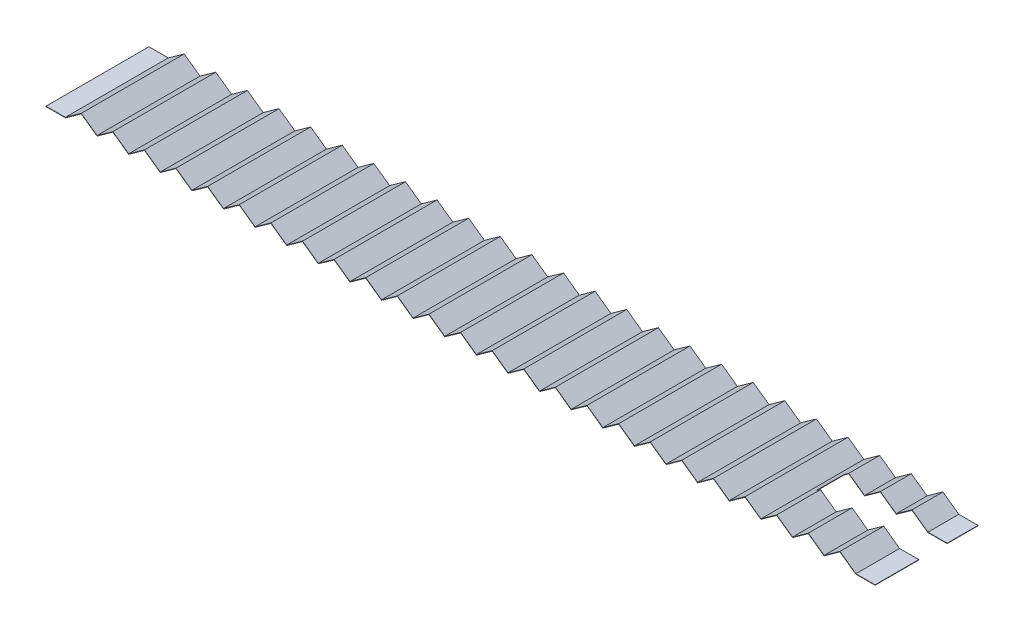
SolidWorks part; units mm, degrees
ref_plane "Front Plane" through (0, 0, 0) normal (0, 0, 1) x (1, 0, 0)
ref_plane "Top Plane" through (0, 0, 0) normal (0, 1, 0) x (1, 0, 0)
ref_plane "Right Plane" through (0, 0, 0) normal (1, 0, 0) x (0, 0, -1)
sketch "Sketch1" plane through (0, 0, 0) normal (0, 0, 1) x (1, 0, 0)
  line L0 (0, 0) -> (12.283, 8.7828)
  line L1 (12.283, 8.7828) -> (24.566, 0)
  line L2 (0, 0) -> (511, 0) construction
  line L3 (24.566, 0) -> (36.849, 8.7828)
  line L4 (36.849, 8.7828) -> (49.132, 0)
  line L5 (49.132, 0) -> (61.415, 8.7828)
  line L6 (61.415, 8.7828) -> (73.698, 0)
  line L7 (73.698, 0) -> (85.981, 8.7828)
  line L8 (85.981, 8.7828) -> (98.264, 0)
  line L9 (98.264, 0) -> (110.547, 8.7828)
  line L10 (110.547, 8.7828) -> (122.83, 0)
  line L11 (122.83, 0) -> (135.113, 8.7828)
  line L12 (135.113, 8.7828) -> (147.396, 0)
  line L13 (147.396, 0) -> (159.679, 8.7828)
  line L14 (159.679, 8.7828) -> (171.962, 0)
  line L15 (171.962, 0) -> (184.245, 8.7828)
  line L16 (184.245, 8.7828) -> (196.528, 0)
  line L17 (196.528, 0) -> (208.811, 8.7828)
  line L18 (208.811, 8.7828) -> (221.094, 0)
  line L19 (0, 0) -> (-15.1, 0)
  line L20 (221.094, 0) -> (233.377, 8.7828)
  line L21 (233.377, 8.7828) -> (245.66, 0)
  line L22 (245.66, 0) -> (257.943, 8.7828)
  line L23 (257.943, 8.7828) -> (270.226, 0)
  line L24 (270.226, 0) -> (282.509, 8.7828)
  line L25 (282.509, 8.7828) -> (294.792, 0)
  line L26 (294.792, 0) -> (307.075, 8.7828)
  line L27 (307.075, 8.7828) -> (319.358, 0)
  line L28 (319.358, 0) -> (331.641, 8.7828)
  line L29 (331.641, 8.7828) -> (343.924, 0)
  line L30 (343.924, 0) -> (356.207, 8.7828)
  line L31 (356.207, 8.7828) -> (368.49, 0)
  line L32 (368.49, 0) -> (380.773, 8.7828)
  line L33 (380.773, 8.7828) -> (393.056, 0)
  line L34 (393.056, 0) -> (405.339, 8.7828)
  line L35 (405.339, 8.7828) -> (417.622, 0)
  line L36 (417.622, 0) -> (429.905, 8.7828)
  line L37 (429.905, 8.7828) -> (442.188, 0)
  line L39 (442.188, 0) -> (454.471, 8.7828)
  line L40 (454.471, 8.7828) -> (466.754, 0)
  line L41 (466.754, 0) -> (479.037, 8.7828)
  line L42 (479.037, 8.7828) -> (491.32, 0)
  line L43 (491.32, 0) -> (503.603, 8.7828)
  line L44 (503.603, 8.7828) -> (515.886, 0)
  line L45 (515.886, 0) -> (528.169, 8.7828)
  line L46 (528.169, 8.7828) -> (540.452, 0)
  line L47 (540.452, 0) -> (552.735, 8.7828)
  line L48 (552.735, 8.7828) -> (565.018, 0)
  line L49 (565.018, 0) -> (577.301, 8.7828)
  line L50 (549.15, -119) -> (549.15, 187) construction
  line L51 (577.301, 8.7828) -> (589.584, 0)
  line L52 (589.584, 0) -> (601.867, 8.7828)
  line L53 (601.867, 8.7828) -> (614.15, 0)
  line L54 (614.15, 0) -> (629.15, 0)
  dimension "D1" = 511
  dimension "D2" = 15.1
  dimension "D3" = 15
  dimension "D4" = 24.566
  dimension "D6" = 80
  dimension "D5" = 25
extrude "Extrude-Thin1" add sketch "Sketch1" along normal mid plane 80 thin thin type one direction reverse wall 0.3
sketch "Sketch2" plane through (0, 0, 0) normal (0, 1, 0) x (1, 0, 0)
  line L1 (549.15, -6) -> (629.15, -6)
  line L2 (549.15, -6) -> (549.15, 16)
  line L3 (549.15, 16) -> (629.15, 16)
  line L4 (629.15, -6) -> (629.15, 16)
  line L5 (549.15, -6) -> (629.15, 16) construction
  line L6 (549.15, 16) -> (629.15, -6) construction
  line L8 (629.15, -40) -> (629.15, 40) construction
  point P0 (589.15, 5)
  dimension "D1" = 80
  dimension "D2" = 22
  dimension "D3" = 5
extrude "Cut-Extrude4" cut sketch "Sketch2" against normal through all and the other way through all contours L1 L4 L3 L2
